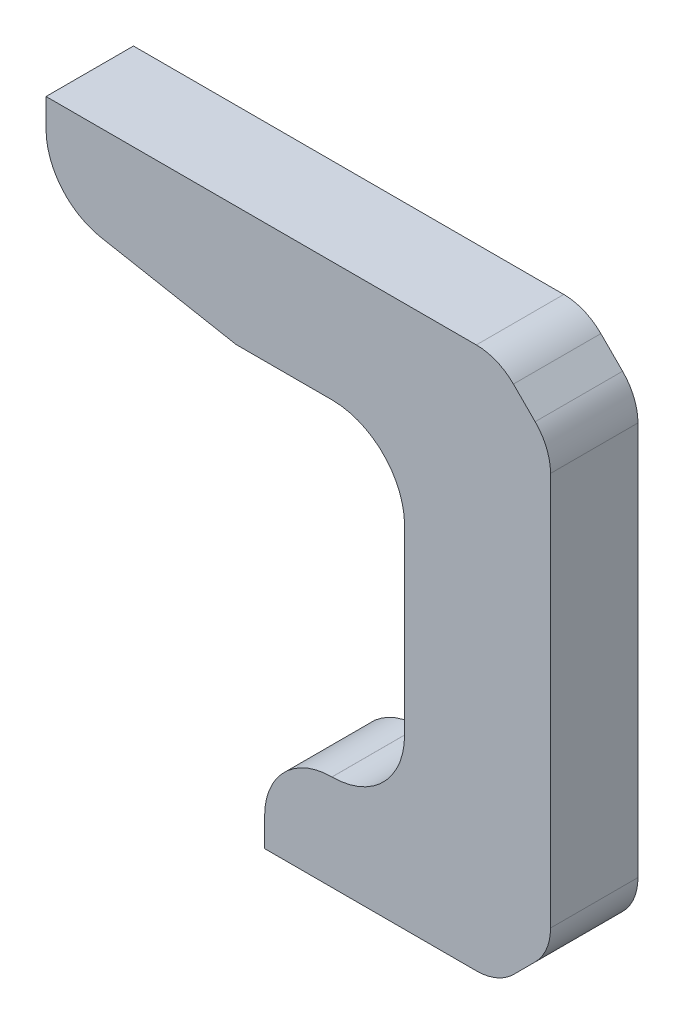
SolidWorks part; units mm, degrees
ref_plane "Plano frontal" through (0, 0, 0) normal (0, 0, 1) x (1, 0, 0)
ref_plane "Plano superior" through (0, 0, 0) normal (0, 1, 0) x (1, 0, 0)
ref_plane "Plano direito" through (0, 0, 0) normal (1, 0, 0) x (0, 0, -1)
sketch "Esboço1" plane through (0, 0, 0) normal (0, 0, 1) x (1, 0, 0)
  line L0 (-16.9933, 40) -> (-16.9933, 19.25) construction
  line L1 (-24.9933, 11.25) -> (-25, 11.25)
  line L2 (-33, 3.25) -> (-33, 0) construction
  line L3 (-33, 0) -> (-8.4853, 0) construction
  line L4 (0, 8.4853) -> (0, 53.5147)
  line L5 (-8.4853, 62) -> (-58, 62) construction
  line L6 (-58, 62) -> (-58, 58.75) construction
  line L7 (-51.4672, 50.8857) -> (-36, 48) construction
  line L8 (-36, 48) -> (-24.9933, 48) construction
  line L9 (-1.7574, 57.7574) -> (-4.2426, 60.2426)
  line L10 (-4.2426, 1.7574) -> (-1.7574, 4.2426)
  line L11 (-57.7, 62) -> (-57.7, 58.75)
  line L12 (-51.4122, 51.1806) -> (-35.9723, 48.3)
  line L13 (-35.9723, 48.3) -> (-24.9933, 48.3)
  line L14 (-16.6933, 40) -> (-16.6933, 19.25)
  line L15 (-24.9933, 10.95) -> (-25, 10.95)
  line L16 (-32.7, 3.25) -> (-32.7, 0)
  line L17 (-32.7, 0) -> (-8.4853, 0)
  line L18 (-57.7, 62) -> (-8.4853, 62)
  line L19 (-16.6933, 41) -> (-14.7433, 41)
  line L20 (-14.7433, 41) -> (-14.7433, 21)
  line L21 (-14.7433, 21) -> (-16.6933, 21)
  arc A0 (-58, 58.75) -> (-51.4672, 50.8857) centre (-50, 58.75) ccw construction
  arc A1 (-16.9933, 19.25) -> (-24.9933, 11.25) centre (-24.9933, 19.25) cw construction
  arc A2 (-25, 11.25) -> (-33, 3.25) centre (-25, 3.25) ccw construction
  arc A3 (-16.9933, 40) -> (-24.9933, 48) centre (-24.9933, 40) ccw construction
  arc A4 (-4.2426, 60.2426) -> (-8.4853, 62) centre (-8.4853, 56) ccw
  arc A5 (-1.7574, 57.7574) -> (0, 53.5147) centre (-6, 53.5147) cw
  arc A6 (-4.2426, 1.7574) -> (-8.4853, 0) centre (-8.4853, 6) cw
  arc A7 (-1.7574, 4.2426) -> (0, 8.4853) centre (-6, 8.4853) ccw
  arc A8 (-57.7, 58.75) -> (-51.4122, 51.1806) centre (-50, 58.75) ccw
  arc A9 (-16.6933, 40) -> (-24.9933, 48.3) centre (-24.9933, 40) ccw
  arc A10 (-16.6933, 19.25) -> (-24.9933, 10.95) centre (-24.9933, 19.25) cw
  arc A11 (-25, 10.95) -> (-32.7, 3.25) centre (-25, 3.25) ccw
  point P3 (0, 62)
  point P5 (0, 0)
  point P19 (0, 31)
  point P28 (-6, 62)
  point P31 (0, 56)
  point P34 (-6, 0)
  point P37 (0, 6)
  point P54 (-14.7433, 31)
  dimension "D1" = 8
  dimension "D2" = 8
  dimension "D11" = 6
  dimension "D3" = 22
  dimension "D4" = 62
  dimension "D5" = 58
  dimension "D6" = 33
  dimension "D7" = 36.75
  dimension "D8" = 3.25
  dimension "D9" = 3.25
  dimension "D10" = 16.9933
  dimension "D13" = 20
  dimension "D14" = 4.5
  dimension "D12" = 0.3
extrude "Ressalto-extrusão1" add sketch "Esboço1" along normal blind 10
sketch "Esboço3" plane through (0, 0, 10) normal (0, 0, 1) x (1, 0, 0)
  line L0 (-16.6933, 40) -> (-16.6933, 19.25) construction
  line L1 (-16.6933, 41) -> (-12.1933, 41)
  line L2 (-16.6933, 41) -> (-16.6933, 21) construction
  line L3 (-16.6933, 21) -> (-12.1933, 21)
  line L4 (-12.1933, 41) -> (-12.1933, 21)
  line L5 (0, 8.4853) -> (0, 53.5147) construction
  line L6 (-16.6933, 41) -> (-18.1933, 41)
  line L7 (-18.1933, 41) -> (-18.1933, 21)
  line L8 (-18.1933, 21) -> (-16.6933, 21)
  point P8 (0, 31)
  point P9 (-16.6933, 31)
  dimension "D1" = 20
  dimension "D2" = 4.5
  dimension "D3" = 6
extrude "Corte-extrusão1" cut sketch "Esboço3" along normal blind 8 from surface at -10 starting at face at (-21.2557, 31.6521, 0)
fillet "Filete1" radius 3 2 edges at (-12.1933, 21, 4) (-12.1933, 41, 4)
